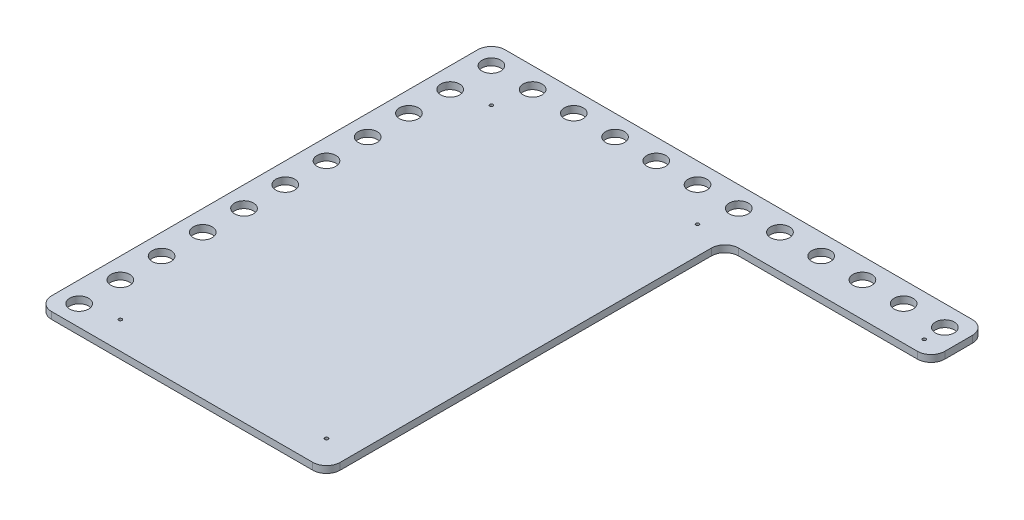
SolidWorks part; units mm, degrees
material "Acrylic (Medium-high impact)"
ref_plane "Front Plane" through (0, 0, 0) normal (0, 0, 1) x (1, 0, 0)
ref_plane "Top Plane" through (0, 0, 0) normal (0, 1, 0) x (1, 0, 0)
ref_plane "Right Plane" through (0, 0, 0) normal (1, 0, 0) x (0, 0, -1)
sketch "Sketch1" plane through (0, 0, 0) normal (0, 1, 0) x (1, 0, 0)
  line L1 (-285.75, -209.55) -> (285.75, -209.55)
  line L2 (-285.75, -209.55) -> (-285.75, 209.55)
  line L3 (-285.75, 209.55) -> (285.75, 209.55)
  line L4 (285.75, -209.55) -> (285.75, 209.55)
  line L5 (-285.75, -209.55) -> (285.75, 209.55) construction
  line L6 (-285.75, 209.55) -> (285.75, -209.55) construction
  point P0 (0, 0)
  dimension "D1" = 419.1
  dimension "D2" = 571.5
extrude "Boss-Extrude1" add sketch "Sketch1" along normal mid plane 6.35
sketch "Sketch2" plane through (0, 3.175, 0) normal (0, 1, 0) x (1, 0, 0)
  line L0 (285.75, 209.55) -> (-285.75, 209.55) construction
  line L1 (-285.75, 209.55) -> (-285.75, -209.55) construction
  line L15 (0, 0) -> (-202.1139, 0) construction
  circle A0 centre (-228.6, 190.5) radius 4.4196
  circle A1 centre (-190.5, 190.5) radius 4.4196
  circle A2 centre (-152.4, 190.5) radius 4.4196
  circle A3 centre (-114.3, 190.5) radius 4.4196
  circle A4 centre (-76.2, 190.5) radius 4.4196
  circle A5 centre (-38.1, 190.5) radius 4.4196
  circle A6 centre (0, 190.5) radius 4.4196
  circle A7 centre (38.1, 190.5) radius 4.4196
  circle A9 centre (-266.7, 38.1) radius 4.4196
  circle A10 centre (-266.7, 76.2) radius 4.4196
  circle A11 centre (-266.7, 114.3) radius 4.4196
  circle A12 centre (-266.7, 152.4) radius 4.4196
  circle A13 centre (-266.7, 190.5) radius 4.4196
  circle A14 centre (-266.7, -190.5) radius 4.4196
  circle A15 centre (-266.7, -152.4) radius 4.4196
  circle A16 centre (-266.7, -114.3) radius 4.4196
  circle A17 centre (-266.7, -76.2) radius 4.4196
  circle A18 centre (-266.7, -38.1) radius 4.4196
  circle A19 centre (-266.7, 0) radius 4.4196
  circle A20 centre (76.2, 190.5) radius 4.4196
  circle A21 centre (114.3, 190.5) radius 4.4196
  circle A22 centre (152.4, 190.5) radius 4.4196
  circle A23 centre (190.5, 190.5) radius 4.4196
  circle A24 centre (228.6, 190.5) radius 4.4196
  circle A25 centre (266.7, 190.5) radius 4.4196
  circle A27 centre (304.8, 190.5) radius 4.4196 [skipped]
  dimension "D2" = 19.05
  dimension "D4" = 8.8392
  dimension "D1" = 16
  dimension "D3" = 19.05
extrude "Cut-Extrude1" cut sketch "Sketch2" against normal through all
sketch "Sketch3" plane through (0, 3.175, 0) normal (0, 1, 0) x (1, 0, 0)
  circle A0 centre (-266.7, 190.5) radius 8.7313
  circle A1 centre (-228.6, 190.5) radius 8.7312
  circle A2 centre (-190.5, 190.5) radius 8.7312
  circle A3 centre (-152.4, 190.5) radius 8.7312
  circle A4 centre (-114.3, 190.5) radius 8.7313
  circle A5 centre (-76.2, 190.5) radius 8.7313
  circle A6 centre (-38.1, 190.5) radius 8.7313
  circle A7 centre (0, 190.5) radius 8.7313
  circle A8 centre (38.1, 190.5) radius 8.7313
  circle A9 centre (76.2, 190.5) radius 8.7313
  circle A10 centre (114.3, 190.5) radius 8.7313
  circle A11 centre (152.4, 190.5) radius 8.7313
  circle A12 centre (190.5, 190.5) radius 8.7313
  circle A13 centre (228.6, 190.5) radius 8.7313
  circle A14 centre (266.7, 190.5) radius 8.7313
  circle A16 centre (-266.7, 152.4) radius 8.7313
  circle A17 centre (-266.7, 114.3) radius 8.7313
  circle A18 centre (-266.7, 76.2) radius 8.7313
  circle A19 centre (-266.7, 38.1) radius 8.7313
  circle A20 centre (-266.7, 0) radius 8.7313
  circle A21 centre (-266.7, -38.1) radius 8.7313
  circle A22 centre (-266.7, -76.2) radius 8.7313
  circle A23 centre (-266.7, -114.3) radius 8.7313
  circle A24 centre (-266.7, -152.4) radius 8.7313
  circle A25 centre (-266.7, -190.5) radius 8.7313
  circle A27 centre (-266.7, -228.6) radius 8.7313 [skipped]
  circle A28 centre (304.8, 190.5) radius 8.7313 [skipped]
  dimension "D1" = 17.4625
  dimension "D2" = 16
  dimension "D3" = 12
extrude "Cut-Extrude2" cut sketch "Sketch3" against normal through all
sketch "Sketch6" [suppressed] plane through (0, 3.175, 0) normal (0, 1, 0) x (1, 0, 0)
  line L0 (285.75, -209.55) -> (285.75, 209.55) construction
  line L1 (146.05, -69.85) -> (285.75, -69.85) construction
  line L2 (146.05, -69.85) -> (146.05, -209.55) construction
  line L3 (146.05, -209.55) -> (285.75, -209.55) construction
  line L4 (285.75, -69.85) -> (285.75, -209.55) construction
  line L5 (-285.75, -209.55) -> (285.75, -209.55) construction
  circle A0 centre (146.05, -69.85) radius 50.8
  dimension "D2" = 101.6
  dimension "D1" = 139.7
extrude "Cut-Extrude4" [suppressed] cut sketch "Sketch6" against normal through all
sketch "Sketch8" plane through (0, 3.175, 0) normal (0, 1, 0) x (1, 0, 0)
  line L0 (-19.05, -209.55) -> (285.75, -209.55)
  line L1 (-285.75, -209.55) -> (285.75, -209.55) construction
  line L2 (285.75, -209.55) -> (285.75, 209.55)
  line L3 (285.75, 209.55) -> (171.45, 209.55)
  line L4 (285.75, 209.55) -> (-285.75, 209.55) construction
  line L5 (171.45, 209.55) -> (171.45, 158.75)
  line L6 (171.45, 158.75) -> (-19.05, 158.75)
  line L7 (-19.05, 158.75) -> (-19.05, -209.55)
  dimension "D1" = 114.3
  dimension "D2" = 50.8
  dimension "D3" = 190.5
extrude "Cut-Extrude5" cut sketch "Sketch8" against normal through all
sketch "Sketch5" plane through (0, 3.175, 0) normal (0, 1, 0) x (1, 0, 0)
  line L0 (-285.75, 209.55) -> (-285.75, -209.55) construction
  line L1 (-44.45, -184.15) -> (-234.95, -184.15) construction
  line L2 (-44.45, -184.15) -> (-44.45, 158.75) construction
  line L3 (-44.45, 158.75) -> (-234.95, 158.75) construction
  line L4 (-234.95, -184.15) -> (-234.95, 158.75) construction
  line L5 (-44.45, -184.15) -> (-234.95, 158.75) construction
  line L6 (-44.45, 158.75) -> (-234.95, -184.15) construction
  line L7 (171.45, 209.55) -> (-285.75, 209.55) construction
  line L8 (-285.75, -209.55) -> (-19.05, -209.55) construction
  line L9 (-19.05, 158.75) -> (-19.05, -209.55) construction
  line L10 (171.45, 209.55) -> (171.45, 158.75) construction
  line L11 (171.45, 209.55) -> (-285.75, 209.55) construction
  circle A0 centre (-234.95, -184.15) radius 1.5113
  circle A1 centre (-234.95, 158.75) radius 1.5113
  circle A2 centre (-44.45, -184.15) radius 1.5113
  circle A3 centre (-44.45, 158.75) radius 1.5113
  circle A4 centre (152.4, 171.45) radius 1.5113
  point P0 (-139.7, -12.7)
  dimension "D3" = 3.0226
  dimension "D1" = 50.8
  dimension "D2" = 50.8
  dimension "D4" = 25.4
  dimension "D5" = 25.4
  dimension "D6" = 19.05
  dimension "D7" = 38.1
extrude "Cut-Extrude3" cut sketch "Sketch5" against normal through all
fillet "Fillet1" radius 12.7 6 edges at (-285.75, 0, -209.55) (-285.75, 0, 209.55) (171.45, 0, -209.55) (171.45, 0, -158.75) (-19.05, 0, -158.75) (-19.05, 0, 209.55)
equation "\"D1@Sketch5\"=\"D2@Sketch5\""
